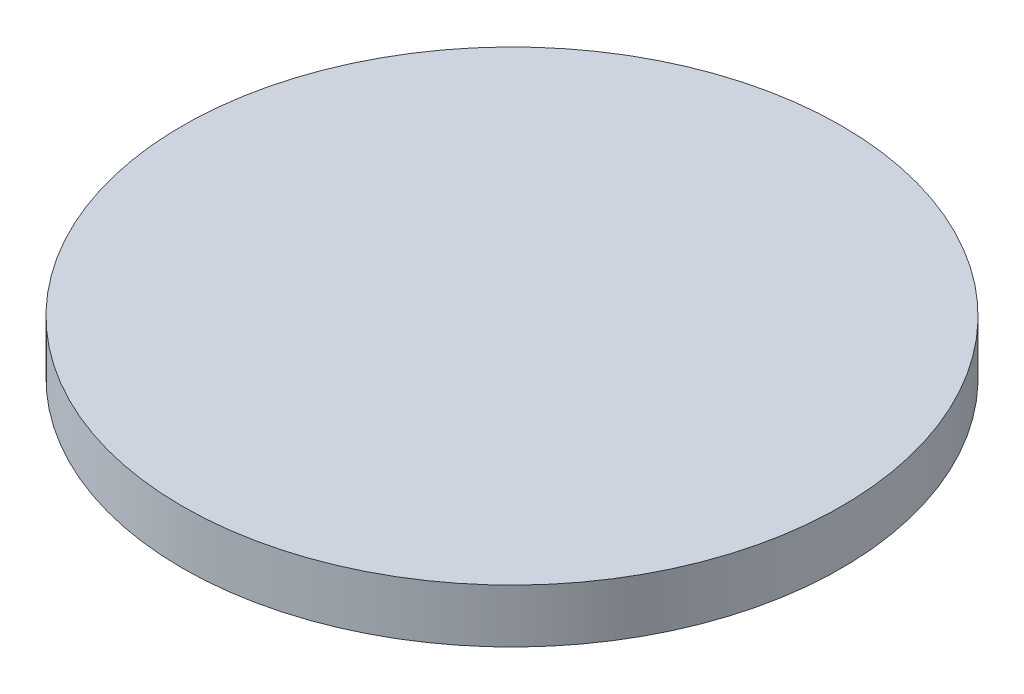
SolidWorks part; units mm, degrees
ref_plane "Plan de face" through (0, 0, 0) normal (0, 0, 1) x (1, 0, 0)
ref_plane "Plan de dessus" through (0, 0, 0) normal (0, 1, 0) x (1, 0, 0)
ref_plane "Plan de droite" through (0, 0, 0) normal (1, 0, 0) x (0, 0, -1)
sketch "Esquisse1" plane through (0, 0, 0) normal (0, 1, 0) x (1, 0, 0)
  circle A0 centre (0, 0) radius 9.525
  dimension "D1" = 19.05
extrude "Boss.-Extru.1" add sketch "Esquisse1" along normal blind 1.55
